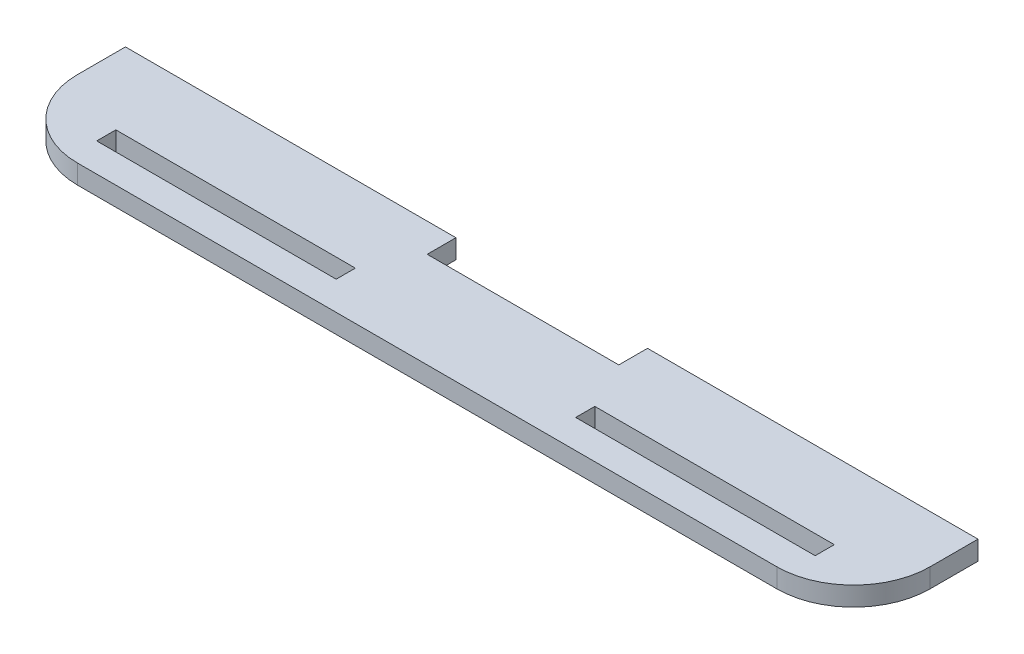
SolidWorks part; units mm, degrees
material "PVC rigido"
ref_plane "Piano frontale" through (0, 0, 0) normal (0, 0, 1) x (1, 0, 0)
ref_plane "Piano superiore" through (0, 0, 0) normal (0, 1, 0) x (1, 0, 0)
ref_plane "Piano destro" through (0, 0, 0) normal (1, 0, 0) x (0, 0, -1)
sketch "Schizzo1" plane through (0, 0, 0) normal (0, 0, 1) x (1, 0, 0)
  line L1 (44.5, 23.5) -> (-44.5, 23.5)
  line L2 (44.5, 23.5) -> (44.5, 21.5)
  line L3 (44.5, 21.5) -> (-44.5, 21.5)
  line L4 (-44.5, 23.5) -> (-44.5, 21.5)
extrude "Estrusione-Estrusione1" add sketch "Schizzo1" along normal up to surface (10 mm away) and the other way up to surface (3 mm away)
sketch "Schizzo2" plane through (0, 21.5, 0) normal (0, -1, 0) x (1, 0, 0)
  line L0 (-37.5, 5) -> (-37.5, 7) construction
  line L1 (-37.5, 5) -> (-12.5, 5)
  line L2 (-37.5, 5) -> (-37.5, 7)
  line L3 (-37.5, 7) -> (-12.5, 7)
  line L4 (-12.5, 5) -> (-12.5, 7)
  line L5 (12.5, 5) -> (37.5, 5)
  line L6 (12.5, 5) -> (12.5, 7)
  line L7 (12.5, 7) -> (37.5, 7)
  line L8 (37.5, 5) -> (37.5, 7)
  line L9 (-37.5, 7) -> (-12.5, 7) construction
extrude "Taglio-Estrusione1" cut sketch "Schizzo2" against normal blind 10
sketch "Schizzo3" plane through (0, 23.5, 0) normal (0, 1, 0) x (1, 0, 0)
  line L0 (44.5, 3) -> (-44.5, 3) construction
  line L1 (10, 3) -> (-10, 3)
  line L2 (10, 3) -> (10, 0)
  line L3 (10, 0) -> (-10, 0)
  line L4 (-10, 3) -> (-10, 0)
  line L5 (10, 3) -> (10, 0) construction
extrude "Taglio-Estrusione2" cut sketch "Schizzo3" against normal blind 10
fillet "Raccordo1" radius 8 2 edges at (-44.5, 22.5, 10) (44.5, 22.5, 10)
